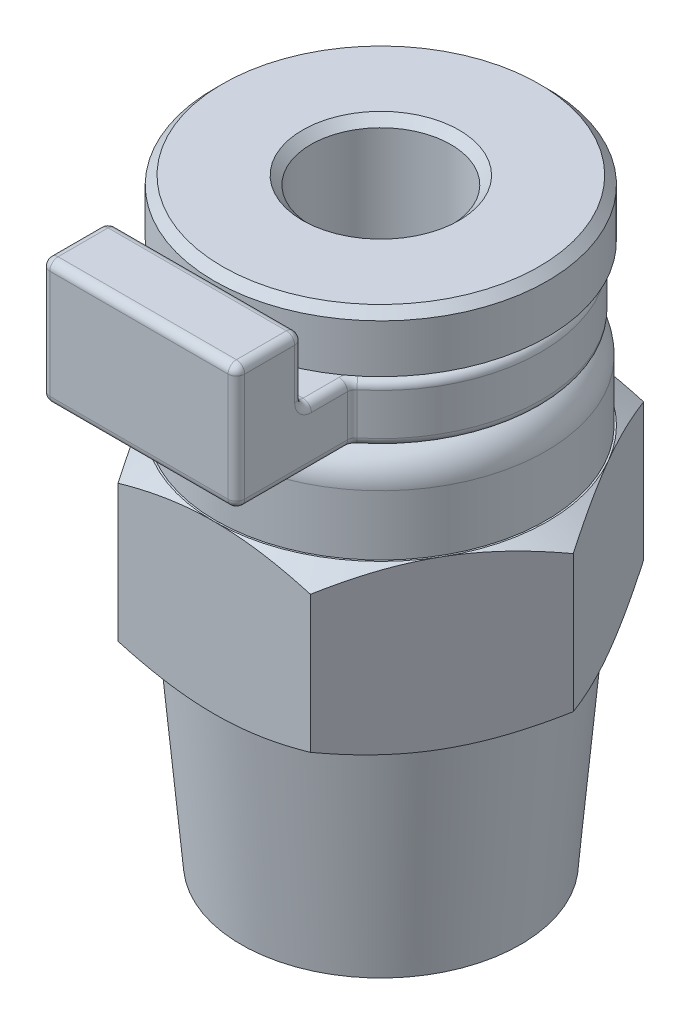
SolidWorks part; units mm, degrees
ref_plane "Front Plane" through (0, 0, 0) normal (0, 0, 1) x (1, 0, 0)
ref_plane "Top Plane" through (0, 0, 0) normal (0, 1, 0) x (1, 0, 0)
ref_plane "Right Plane" through (0, 0, 0) normal (1, 0, 0) x (0, 0, -1)
sketch "Sketch1" plane through (0, 0, 0) normal (0, 1, 0) x (1, 0, 0)
  line L1 (5.7735, 0) -> (2.8868, 5)
  line L2 (2.8868, 5) -> (-2.8868, 5)
  line L3 (-2.8868, 5) -> (-5.7735, 0)
  line L4 (-5.7735, 0) -> (-2.8868, -5)
  line L5 (-2.8868, -5) -> (2.8868, -5)
  line L6 (2.8868, -5) -> (5.7735, 0)
  circle A0 centre (0, 0) radius 5 construction
  dimension "D1" = 10
extrude "Boss-Extrude1" add sketch "Sketch1" along normal mid plane 5
sketch "Sketch2" plane through (0, 2.5, 0) normal (0, 1, 0) x (1, 0, 0)
  line L0 (-2.8868, -5) -> (2.8868, -5) construction
  circle A0 centre (0, 0) radius 5
extrude "Cut-Extrude4" cut sketch "Sketch2" against normal blind 2.8 draft 60 flip side to cut contours A0
mirror "Mirror1" about plane through (0, 0, 0) normal (0, 1, 0) of "Cut-Extrude4"
sketch "Sketch3" plane through (0, 2.5, 0) normal (0, 1, 0) x (1, 0, 0)
  circle A0 centre (0, 0) radius 4.95
  dimension "D1" = 9.9
extrude "Boss-Extrude2" add sketch "Sketch3" along normal blind 2.8 contours A0
fillet "Fillet1" radius 1 1 edges at (0, 5.3, 4.95)
sketch "Sketch4" plane through (0, 5.3, 0) normal (0, 1, 0) x (1, 0, 0)
  circle A0 centre (0, 0) radius 2.8
  dimension "D1" = 5.6
extrude "Boss-Extrude3" add sketch "Sketch4" along normal blind 2 separate body
sketch "Sketch6" plane through (0, 7.3, 0) normal (0, 1, 0) x (1, 0, 0)
  circle A0 centre (0, 0) radius 5
  dimension "D1" = 10
extrude "Boss-Extrude4" add sketch "Sketch6" along normal blind 1.7
sketch "Sketch8" plane through (0, -2.5, 0) normal (0, -1, 0) x (1, 0, 0)
  circle A0 centre (0, 0) radius 4.75
  dimension "D1" = 9.5
extrude "Boss-Extrude5" add sketch "Sketch8" along normal blind 6.4 draft 5
sketch "Sketch7" plane through (0, 9, 0) normal (0, 1, 0) x (1, 0, 0)
  circle A0 centre (0, 0) radius 2.1
  dimension "D1" = 4.2
extrude "Cut-Extrude5" cut sketch "Sketch7" against normal through all
chamfer "Chamfer1" distance 0.25 angle 45 2 edges at (0, 9, 5) (0, 9, 2.1)
sketch "Sketch9" plane through (0, 5.3, 0) normal (0, 1, 0) x (1, 0, 0)
  line L0 (0, 0) -> (0, 4.8) construction
  line L1 (-2.25, 4.24) -> (-2.25, 1.6666)
  line L6 (2.25, 4.24) -> (2.25, 1.6666)
  line L7 (-2.925, -3.8058) -> (-2.925, -7.26)
  line L8 (-2.925, -7.26) -> (2.925, -7.26)
  line L9 (2.925, -7.26) -> (2.925, -3.8058)
  circle A0 centre (0, 0) radius 2.8 construction
  arc A1 (-2.25, 1.6666) -> (2.25, 1.6666) centre (0, 0) ccw
  arc A2 (-2.25, 4.24) -> (-2.925, -3.8058) centre (0, 0) ccw
  circle A3 centre (0, 0) radius 4.8 construction
  circle A4 centre (0, 0) radius 2.8 construction
  arc A5 (2.925, -3.8058) -> (2.25, 4.24) centre (0, 0) ccw
  dimension "D2" = 4.5
  dimension "D3" = 11.5
  dimension "D4" = 5.85
  dimension "D1" = 2
extrude "Boss-Extrude6" add sketch "Sketch9" along normal blind 1.75 separate body contours L1 A1 L6 A5 L9 L8 L7 A2
sketch "Sketch10" plane through (0, 7.05, 0) normal (0, 1, 0) x (1, 0, 0)
  line L0 (2.925, -7.26) -> (2.925, -3.8058) construction
  line L1 (-2.925, -7.26) -> (2.925, -7.26)
  line L2 (-2.925, -7.26) -> (-2.925, -5.26)
  line L3 (-2.925, -5.26) -> (2.925, -5.26)
  line L4 (2.925, -7.26) -> (2.925, -5.26)
  dimension "D1" = 2
extrude "Boss-Extrude7" add sketch "Sketch10" along normal blind 2
fillet "Fillet2" radius 0.25 30 edges at (0, 9.05, 5.26) (2.925, 9.05, 6.26) (0, 9.05, 7.26) (-2.925, 9.05, 6.26) (-2.925, 5.3, 5.5329) (0, 5.3, 7.26) (2.925, 5.3, 5.5329) (4.7832, 5.3, -0.4013) (2.25, 5.3, -2.9533) (0, 5.3, 2.8) (-2.25, 5.3, -2.9533) (-4.7832, 5.3, -0.4013) (-2.925, 7.05, 4.5329) (-4.7832, 7.05, -0.4013) (-2.25, 7.05, -2.9533) (0, 7.05, 2.8) (2.25, 7.05, -2.9533) (4.7832, 7.05, -0.4013) (2.925, 7.05, 4.5329) (0, 7.05, 5.26) (2.925, 7.175, 7.26) (-2.925, 7.175, 7.26) (-2.925, 8.05, 5.26) (-2.925, 6.175, 3.8058) (-2.25, 6.175, -1.6666) (2.25, 6.175, -1.6666) (2.25, 6.175, -4.24) (2.925, 6.175, 3.8058) (2.925, 8.05, 5.26) (-2.25, 6.175, -4.24)
